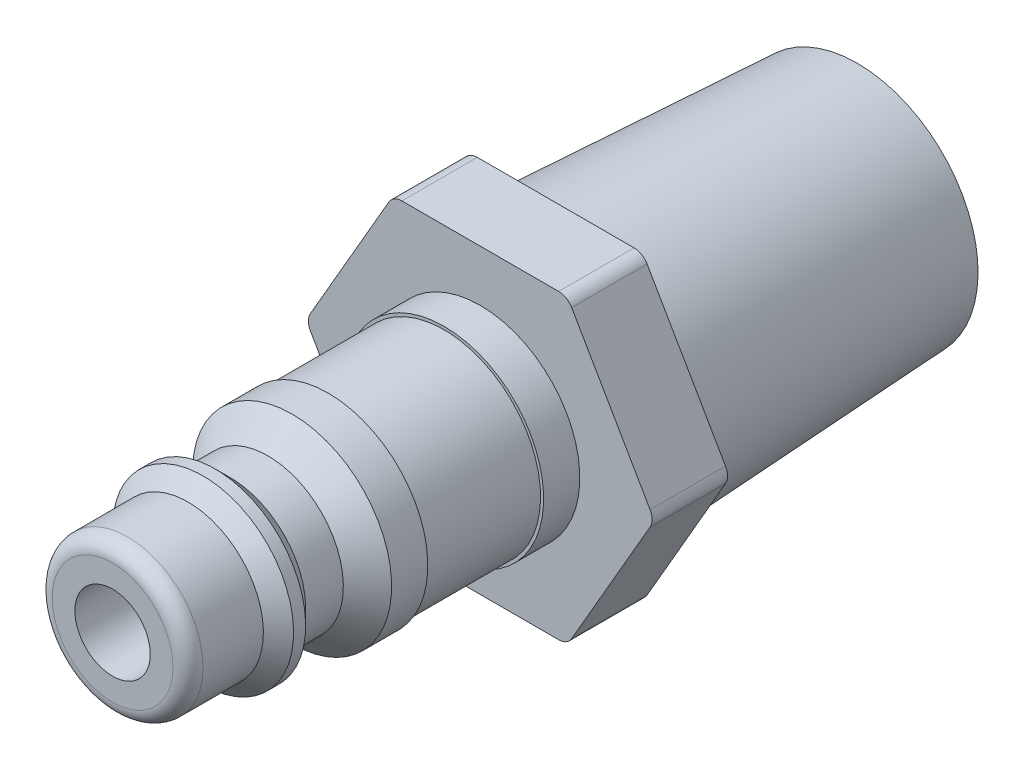
SolidWorks part; units mm, degrees
ref_plane "Front Plane" through (0, 0, 0) normal (0, 0, 1) x (1, 0, 0)
ref_plane "Top Plane" through (0, 0, 0) normal (0, 1, 0) x (1, 0, 0)
ref_plane "Right Plane" through (0, 0, 0) normal (1, 0, 0) x (0, 0, -1)
sketch "Sketch1" plane through (0, 0, 0) normal (1, 0, 0) x (0, 0, -1)
  line L0 (3.175, 3.175) -> (3.81, 3.81)
  line L1 (12.7, 0) -> (31.3531, 0)
  line L2 (0, 1.5875) -> (0, 3.175)
  line L3 (0, 3.175) -> (3.175, 3.175)
  line L4 (31.3531, 0) -> (31.3531, 14.3659)
  line L5 (3.81, 3.81) -> (4.318, 3.81)
  line L10 (4.318, 3.81) -> (4.953, 3.175)
  line L11 (4.953, 3.175) -> (6.5405, 3.175)
  line L12 (6.5405, 3.175) -> (7.5565, 4.191)
  line L13 (7.5565, 4.191) -> (9.0805, 4.191)
  line L14 (15.4781, 4.191) -> (15.4781, 14.3659)
  line L15 (15.4781, 14.3659) -> (31.3531, 14.3659)
  line L16 (0, 1.5875) -> (12.7, 1.5875)
  line L17 (12.7, 1.5875) -> (12.7, 0)
  line L18 (13.9541, 4.191) -> (15.4781, 4.191)
  line L20 (9.0805, 4.191) -> (9.0805, 4.064)
  line L21 (9.0805, 4.064) -> (13.9541, 4.064)
  line L22 (13.9541, 4.191) -> (13.9541, 4.064)
  dimension "D1" = 31.3531
  dimension "D2" = 1.5875
  dimension "D3" = 3.175
  dimension "D4" = 3.175
  dimension "D5" = 0.635
  dimension "D6" = 45
  dimension "D7" = 0.508
  dimension "D8" = 1.5875
  dimension "D9" = 1.016
  dimension "D10" = 0.127
  dimension "D11" = 1.524
  dimension "D12" = 1.524
  dimension "D13" = 12.7
  dimension "D14" = 15.875
revolve "Revolve1" add sketch "Sketch1" angle 360 about L1
sketch "Sketch2" plane through (0, 0, -15.4781) normal (0, 0, -1) x (-1, 0, 0)
  line L1 (7.3323, 0) -> (3.6662, 6.35)
  line L2 (3.6662, 6.35) -> (-3.6662, 6.35)
  line L3 (-3.6662, 6.35) -> (-7.3323, 0)
  line L4 (-7.3323, 0) -> (-3.6662, -6.35)
  line L5 (-3.6662, -6.35) -> (3.6662, -6.35)
  line L6 (3.6662, -6.35) -> (7.3323, 0)
  circle A0 centre (0, 0) radius 6.35 construction
  circle A1 centre (0, 0) radius 31.7328
  dimension "D1" = 12.7
extrude "Cut-Extrude1" cut sketch "Sketch2" along normal through all
sketch "Sketch3" plane through (0, 0, -31.3531) normal (0, 0, -1) x (-1, 0, 0)
  circle A0 centre (0, 0) radius 11.1202
  circle A1 centre (0, 0) radius 5.08
  dimension "D1" = 10.16
extrude "Cut-Extrude2" cut sketch "Sketch3" against normal blind 12.7 draft 3
fillet "Fillet1" radius 0.635 7 edges at (0, -3.175, 0) (-3.6662, 6.35, -17.0656) (-7.3323, 0, -17.0656) (-3.6662, -6.35, -17.0656) (3.6662, -6.35, -17.0656) (7.3323, 0, -17.0656) (3.6662, 6.35, -17.0656)
